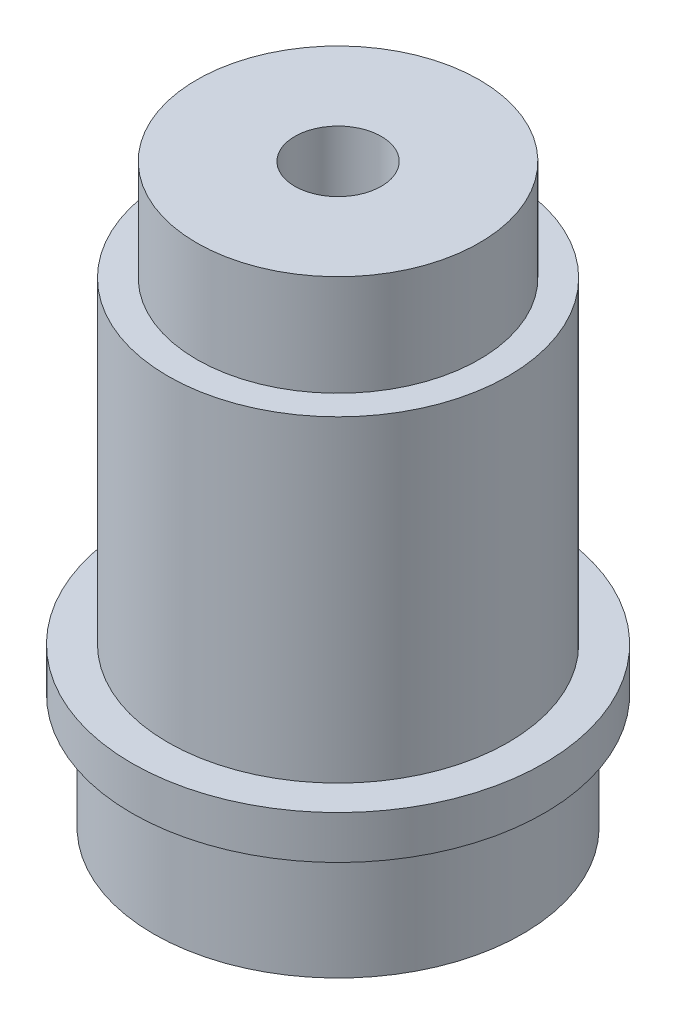
SolidWorks part; units mm, degrees
material "5052-H34"
ref_plane "正面" through (0, 0, 0) normal (0, 0, 1) x (1, 0, 0)
ref_plane "平面" through (0, 0, 0) normal (0, 1, 0) x (1, 0, 0)
ref_plane "右側面" through (0, 0, 0) normal (1, 0, 0) x (0, 0, -1)
sketch "ｽｹｯﾁ1" plane through (0, 0, 0) normal (0, 1, 0) x (1, 0, 0)
  circle A0 centre (0, 0) radius 6.4
  dimension "D1" = 12.8
extrude "ﾎﾞｽ - 押し出し1" add sketch "ｽｹｯﾁ1" along normal blind 4
sketch "ｽｹｯﾁ2" plane through (0, 4, 0) normal (0, 1, 0) x (1, 0, 0)
  circle A0 centre (0, 0) radius 7.15
  dimension "D1" = 14.3
extrude "ﾎﾞｽ - 押し出し2" add sketch "ｽｹｯﾁ2" along normal blind 1.5
sketch "ｽｹｯﾁ3" plane through (0, 5.5, 0) normal (0, 1, 0) x (1, 0, 0)
  circle A0 centre (0, 0) radius 5.9
  dimension "D1" = 11.8
extrude "ﾎﾞｽ - 押し出し3" add sketch "ｽｹｯﾁ3" along normal blind 11
sketch "ｽｹｯﾁ4" plane through (0, 16.5, 0) normal (0, 1, 0) x (1, 0, 0)
  circle A0 centre (0, 0) radius 4.9
  dimension "D1" = 9.8
extrude "ﾎﾞｽ - 押し出し4" add sketch "ｽｹｯﾁ4" along normal blind 3.5
sketch "ｽｹｯﾁ5" plane through (0, 0, 0) normal (0, -1, 0) x (-1, 0, 0)
  circle A0 centre (0, 0) radius 5
  dimension "D1" = 10
extrude "ｶｯﾄ - 押し出し1" cut sketch "ｽｹｯﾁ5" against normal blind 15
sketch "ｽｹｯﾁ6" plane through (0, 20, 0) normal (0, 1, 0) x (1, 0, 0)
  circle A0 centre (0, 0) radius 1.5
  dimension "D1" = 3
extrude "ｶｯﾄ - 押し出し2" cut sketch "ｽｹｯﾁ6" against normal up to surface (5 mm away) up to face at (0, 15, -5)
